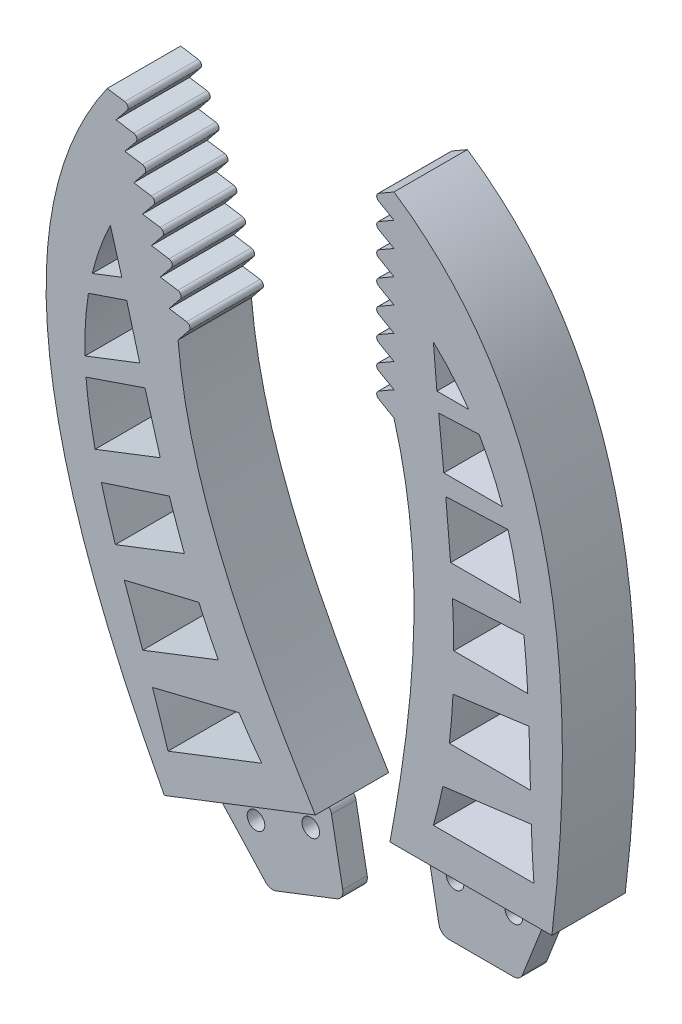
SolidWorks part; units mm, degrees
ref_plane "前视基准面" through (0, 0, 0) normal (0, 0, 1) x (1, 0, 0)
ref_plane "上视基准面" through (0, 0, 0) normal (0, 1, 0) x (1, 0, 0)
ref_plane "右视基准面" through (0, 0, 0) normal (1, 0, 0) x (0, 0, -1)
other "Configuration Table"
sketch "草图2" plane through (0, 0, 0) normal (0, 0, 1) x (1, 0, 0)
  line L0 (1.6604, 0) -> (14.9159, 0)
  line L5 (-0.3054, 1.6321) -> (-2.5923, 13.8521)
  line L6 (16.7779, 1.2699) -> (21.5694, 13.4899)
  line L7 (-0.6265, 16.22) -> (19.7074, 16.22)
  line L8 (2.987, 11.22) -> (14.987, 11.22) construction
  arc A0 (1.6604, 0) -> (-0.3054, 1.6321) centre (1.6604, 2) cw
  arc A1 (14.9159, 0) -> (16.7779, 1.2699) centre (14.9159, 2) ccw
  arc A2 (21.5694, 13.4899) -> (19.7074, 16.22) centre (19.7074, 14.22) ccw
  arc A3 (-2.5923, 13.8521) -> (-0.6265, 16.22) centre (-0.6265, 14.22) cw
  circle A4 centre (2.987, 11.22) radius 1.8
  circle A6 centre (14.987, 11.22) radius 1.8
  point P7 (0, 0)
  dimension "D4" = 2
  dimension "D6" = 3.6
  dimension "D10" = 3.6
  dimension "D1" = 111.41
  dimension "D2" = 100.6
  dimension "D3" = 16.22
  dimension "D7" = 5
  dimension "D8" = 5
  dimension "D9" = 12
extrude "凸台-拉伸1" add sketch "草图2" along normal blind 5
ref_plane "基准面1" through (0, 0, -5) normal (0, 0, -1) x (-1, 0, 0)
sketch "草图3" plane through (0, 0, -5) normal (0, 0, -1) x (-1, 0, 0)
  line L0 (0.6265, 16.22) -> (-27.7726, 16.22)
  line L2 (4.4918, 137.7978) -> (4.4918, 131.6636)
  line L3 (5.3189, 16.22) -> (0.6265, 16.22)
  line L4 (4.4918, 131.6636) -> (7.622, 129.8565)
  line L5 (-24.1038, 23.6118) -> (-3.5582, 23.6118)
  line L7 (7.622, 128.4708) -> (4.4918, 126.6636)
  line L8 (7.622, 123.4708) -> (4.4918, 121.6636)
  line L9 (4.4918, 126.6636) -> (7.622, 124.8565)
  line L10 (7.622, 118.4708) -> (4.4918, 116.6636)
  line L11 (4.4918, 121.6636) -> (7.622, 119.8565)
  line L12 (7.622, 113.4708) -> (4.4918, 111.6636)
  line L13 (4.4918, 116.6636) -> (7.622, 114.8565)
  line L14 (7.622, 108.4708) -> (4.4918, 106.6636)
  line L15 (4.4918, 111.6636) -> (7.622, 109.8565)
  line L16 (7.622, 103.4708) -> (4.4918, 101.6636)
  line L17 (4.4918, 106.6636) -> (7.622, 104.8565)
  line L18 (7.622, 98.4708) -> (4.4918, 96.6636)
  line L19 (4.4918, 101.6636) -> (7.622, 99.8565)
  line L20 (7.622, 93.4708) -> (4.4918, 91.6636)
  line L21 (4.4918, 96.6636) -> (7.622, 94.8565)
  arc A0 (7.622, 129.8565) -> (7.622, 128.4708) centre (7.222, 129.1636) cw
  arc A1 (7.622, 124.8565) -> (7.622, 123.4708) centre (7.222, 124.1636) cw
  arc A2 (7.622, 119.8565) -> (7.622, 118.4708) centre (7.222, 119.1636) cw
  arc A3 (7.622, 114.8565) -> (7.622, 113.4708) centre (7.222, 114.1636) cw
  arc A4 (7.622, 109.8565) -> (7.622, 108.4708) centre (7.222, 109.1636) cw
  arc A5 (7.622, 104.8565) -> (7.622, 103.4708) centre (7.222, 104.1636) cw
  arc A6 (7.622, 99.8565) -> (7.622, 98.4708) centre (7.222, 99.1636) cw
  arc A7 (7.622, 94.8565) -> (7.622, 93.4708) centre (7.222, 94.1636) cw
  spline S0 degree 3 poles (-27.7726, 16.22) (-32.4932, 55.4675) (-32.4536, 107.0772) (4.4918, 131.6636) knots 0 0 0 0 1 1 1 1
  spline S1 degree 3 poles (4.4918, 91.6636) (-2.5851, 67.2009) (0.7184, 40.72) (5.3189, 16.22) knots 0 0 0 0 1 1 1 1
  spline S2 degree 3 poles (-24.1038, 23.6118) (-21.8505, 52.3652) (-27.0309, 87.116) (-3.5582, 109.1636) knots 0 0 0 0 1 1 1 1
  spline S3 degree 3 poles (-3.5582, 109.1636) (-5.6867, 80.926) (-11.7667, 51.5274) (-3.5582, 23.6118) knots 0 0 0 0 1 1 1 1
  point P21 (8.822, 129.1636)
  point P22 (0, 81.1226)
  point P24 (4.8083, 146.7572)
  point P33 (4.4918, 131.6636)
  point P38 (1.8953, 80.0343)
  point P43 (0.6265, 51.8179)
  point P48 (-3.5582, 124.1636)
  point P53 (-6.6203, 77.4716)
  point P55 (-7.2781, 44.2521)
  point P58 (0, 0)
  point P59 (-16.9808, 88.9833)
  point P60 (-23.0655, 51.8179)
  point P61 (-3.5582, 109.1636)
  dimension "D3" = 0.8
  dimension "D1" = 60
  dimension "D2" = 5
  dimension "D4" = 5
extrude "凸台-拉伸2" add sketch "草图3" against normal blind 15
sketch "草图5" plane through (0, 0, -5) normal (0, 0, -1) x (-1, 0, 0)
  line L0 (-24.9087, 33.9734) -> (-5.5019, 31.4842)
  line L1 (-24.9087, 39.7319) -> (-5.5019, 39.7319)
  line L2 (-24.9087, 39.7319) -> (-24.9087, 33.9734)
  line L4 (-5.5019, 39.7319) -> (-5.5019, 31.4842)
  line L5 (-23.1435, 56.5607) -> (-7.5693, 56.5607)
  line L6 (-23.1435, 56.5607) -> (-23.1435, 50.9092)
  line L8 (-7.5693, 56.5607) -> (-7.5693, 48.8208)
  line L9 (-22.5876, 71.8596) -> (-5.89, 71.8596)
  line L10 (-22.5876, 71.8596) -> (-22.5876, 66.5555)
  line L12 (-5.89, 71.8596) -> (-5.89, 65.6223)
  line L13 (-21.1583, 87.0408) -> (-4.7223, 87.0408)
  line L14 (-21.1583, 87.0408) -> (-21.1583, 83.6728)
  line L16 (-4.7223, 87.0408) -> (-4.7223, 82.9911)
  line L17 (-13.5164, 100.8098) -> (-3.174, 100.8098)
  line L18 (-13.5164, 100.8098) -> (-13.5164, 97.4892)
  line L20 (-3.174, 100.8098) -> (-3.174, 97.0449)
  line L21 (-23.1435, 50.9092) -> (-7.5693, 48.8208)
  line L22 (-22.5876, 66.5555) -> (-5.89, 65.6223)
  line L23 (-21.1583, 83.6728) -> (-4.7223, 82.9911)
  line L24 (-13.5164, 97.4892) -> (-3.174, 97.0449)
  spline S0 degree 3 poles (-3.5582, 109.1636) (-5.6867, 80.926) (-11.7667, 51.5274) (-3.5582, 23.6118) knots 0 0 0 0 1 1 1 1 construction
extrude "凸台-拉伸5" add sketch "草图5" against normal blind 15
ref_plane "基准面2" through (-9.8294, -1.8395, 0) normal (-0.9829, -0.184, 0) x (0, 0, 1)
mirror "镜向3" about plane through (-9.8294, -1.8395, 0) normal (-0.9829, -0.184, 0) of bodies 108
